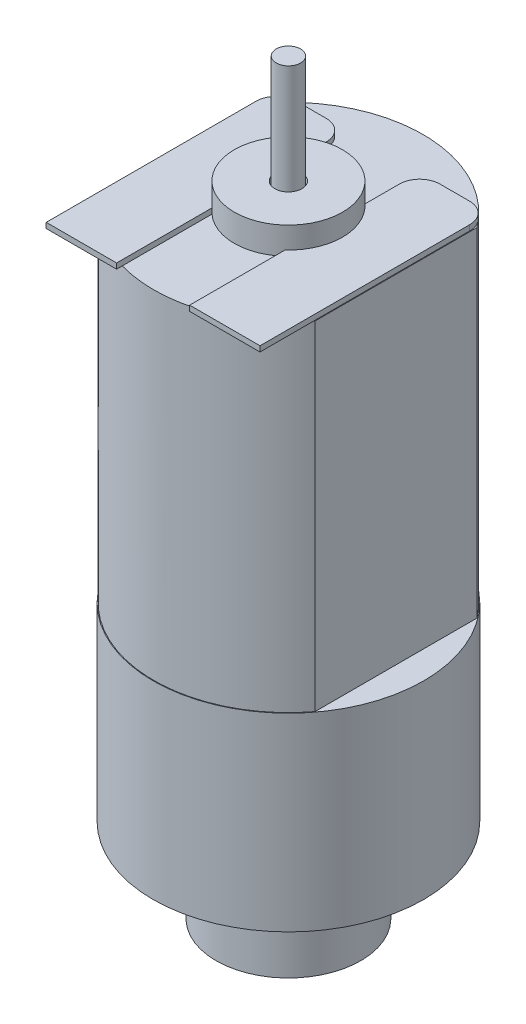
SolidWorks part; units mm, degrees
ref_plane "Front Plane" through (0, 0, 0) normal (0, 0, 1) x (1, 0, 0)
ref_plane "Top Plane" through (0, 0, 0) normal (0, 1, 0) x (1, 0, 0)
ref_plane "Right Plane" through (0, 0, 0) normal (1, 0, 0) x (0, 0, -1)
sketch "Sketch2" plane through (0, 0, 0) normal (0, 1, 0) x (1, 0, 0)
  circle A0 centre (0, 0) radius 5
  dimension "D1" = 10
extrude "Boss-Extrude1" add sketch "Sketch2" along normal blind 7
sketch "Sketch3" plane through (0, 7, 0) normal (0, 1, 0) x (1, 0, 0)
  line L2 (-3.975, 2.9917) -> (-3.975, -2.9917)
  line L4 (3.975, 2.9917) -> (3.975, -2.9917)
  line L5 (-3.975, 5.437) -> (3.975, -5.437) construction
  line L6 (-3.975, -5.437) -> (3.975, 5.437) construction
  arc A0 (-3.975, -2.9917) -> (3.975, -2.9917) centre (0, 0) ccw
  arc A1 (3.975, 2.9917) -> (-3.975, 2.9917) centre (0, 0) ccw
  point P7 (-4.975, 0)
  dimension "D1" = 9.95
  dimension "D2" = 1
extrude "Boss-Extrude2" add sketch "Sketch3" along normal blind 12.5
sketch "Sketch4" plane through (0, 19.5, 0) normal (0, 1, 0) x (1, 0, 0)
  line L0 (0, -5.9807) -> (0, 5.9807) construction
  line L5 (-3.2, 3.5) -> (-2.1, 3.5)
  line L6 (-3.95, 2.75) -> (-3.95, -5)
  line L7 (-3.95, -5) -> (-1.35, -5)
  line L8 (-1.35, 2.75) -> (-1.35, -5)
  line L9 (-3.95, 3.5) -> (-1.35, -5) construction
  line L10 (-3.95, -5) -> (-1.35, 3.5) construction
  line L11 (3.95, -5) -> (1.35, -5)
  line L12 (1.35, 2.75) -> (1.35, -5)
  line L13 (3.2, 3.5) -> (2.1, 3.5)
  line L14 (3.95, 2.75) -> (3.95, -5)
  arc A0 (-1.35, 2.75) -> (-2.1, 3.5) centre (-2.1, 2.75) ccw
  arc A1 (-3.2, 3.5) -> (-3.95, 2.75) centre (-3.2, 2.75) ccw
  arc A2 (1.35, 2.75) -> (2.1, 3.5) centre (2.1, 2.75) cw
  arc A3 (3.2, 3.5) -> (3.95, 2.75) centre (3.2, 2.75) cw
  point P0 (-2.65, -0.75)
  dimension "D5" = 0.75
  dimension "D1" = 2.6
  dimension "D2" = 2.65
  dimension "D3" = 5
  dimension "D4" = 3.5
extrude "Boss-Extrude3" add sketch "Sketch4" along normal blind 0.2
sketch "Sketch5" plane through (0, 19.5, 0) normal (0, 1, 0) x (1, 0, 0)
  circle A0 centre (0, 0) radius 2
  dimension "D1" = 4
extrude "Boss-Extrude4" add sketch "Sketch5" along normal blind 1
sketch "Sketch6" plane through (0, 20.5, 0) normal (0, 1, 0) x (1, 0, 0)
  circle A0 centre (0, 0) radius 0.5
  dimension "D1" = 1
extrude "Cut-Extrude1" cut sketch "Sketch6" against normal blind 2
sketch "Sketch7" plane through (0, 18.5, 0) normal (0, 1, 0) x (1, 0, 0)
  circle A0 centre (0, 0) radius 0.45
  dimension "D1" = 0.9
extrude "Boss-Extrude5" add sketch "Sketch7" along normal blind 6
sketch "Sketch8" plane through (0, 0, 0) normal (0, -1, 0) x (1, 0, 0)
  circle A0 centre (0, 0) radius 3.5
  dimension "D1" = 7
extrude "Boss-Extrude6" add sketch "Sketch8" along normal blind 0.02
sketch "Sketch9" plane through (0, -0.02, 0) normal (0, -1, 0) x (1, 0, 0)
  circle A0 centre (0, 0) radius 2.675
  dimension "D1" = 5.35
extrude "Boss-Extrude7" add sketch "Sketch9" along normal blind 3.1
sketch "Sketch10" plane through (0, -3.12, 0) normal (0, -1, 0) x (1, 0, 0)
  circle A0 centre (0, 0) radius 1.675
  circle A1 centre (0, 0) radius 2.675 construction
  dimension "D1" = 1
extrude "Cut-Extrude2" cut sketch "Sketch10" against normal blind 2
